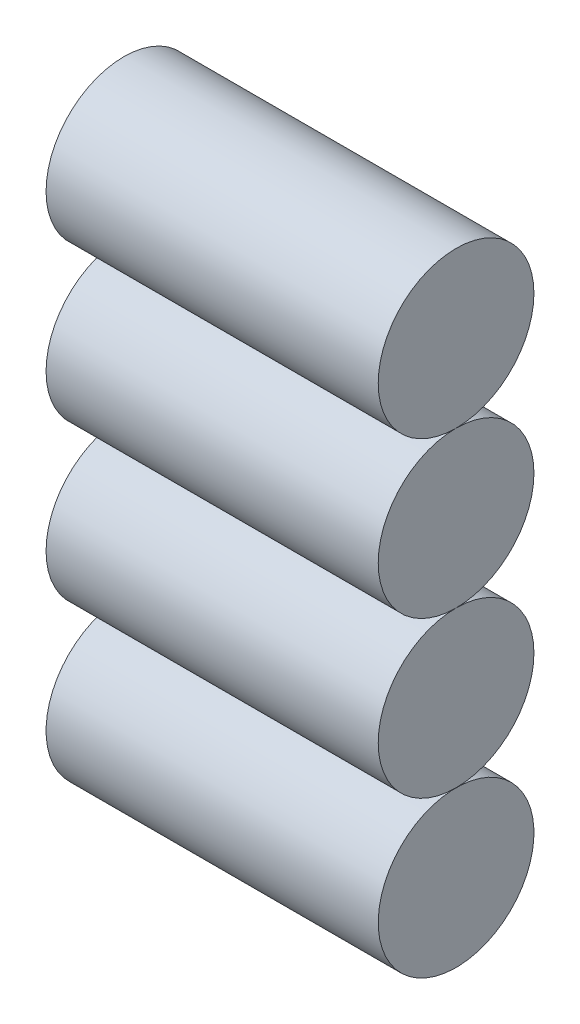
SolidWorks part; units mm, degrees
ref_plane "Front Plane" through (0, 0, 0) normal (0, 0, 1) x (1, 0, 0)
ref_plane "Top Plane" through (0, 0, 0) normal (0, 1, 0) x (1, 0, 0)
ref_plane "Right Plane" through (0, 0, 0) normal (1, 0, 0) x (0, 0, -1)
sketch "Sketch2" plane through (0, 0, 0) normal (0, 1, 0) x (1, 0, 0)
  line L1 (-36, -17.5) -> (36, -17.5)
  line L2 (-36, -17.5) -> (-36, 17.5)
  line L3 (-36, 17.5) -> (36, 17.5)
  line L4 (36, -17.5) -> (36, 17.5)
  line L5 (-36, -17.5) -> (36, 17.5) construction
  line L6 (-36, 17.5) -> (36, -17.5) construction
  point P0 (0, 0)
  dimension "D1" = 72
  dimension "D2" = 35
extrude "Boss-Extrude1" add sketch "Sketch2" along normal blind 135
sketch "Sketch3" plane through (-36, 0, 0) normal (-1, 0, 0) x (0, 0, 1)
  line L1 (-17.5, 135) -> (-17.5, 0) construction
  line L2 (-17.5, 135) -> (17.5, 135) construction
  line L4 (-17.5, 135) -> (17.5, 135)
  line L5 (-17.5, 135) -> (-17.5, 0)
  line L6 (-17.5, 0) -> (17.5, 0)
  line L7 (17.5, 135) -> (17.5, 0)
  circle A0 centre (-0.6236, 16.8649) radius 16.8764
  circle A1 centre (-0.6236, 50.6178) radius 16.8764
  circle A2 centre (-0.6236, 84.3707) radius 16.8764
  circle A5 centre (-0.6236, 118.1236) radius 16.8764
  line M5 (-17.5, 0) -> (17.5, 0)
  line M6 (17.5, 0) -> (17.5, 135)
  line M7 (17.5, 135) -> (-17.5, 135)
  line M8 (-17.5, 135) -> (-17.5, 0)
extrude "Cut-Extrude1" cut sketch "Sketch3" against normal blind 135 contours A5 L5 A2 | A5 L4 M8 | A5 A2 A1 A0 M5 M6 M7 | A2 L5 A1 | A1 L5 A0 | A0 L5 M5
